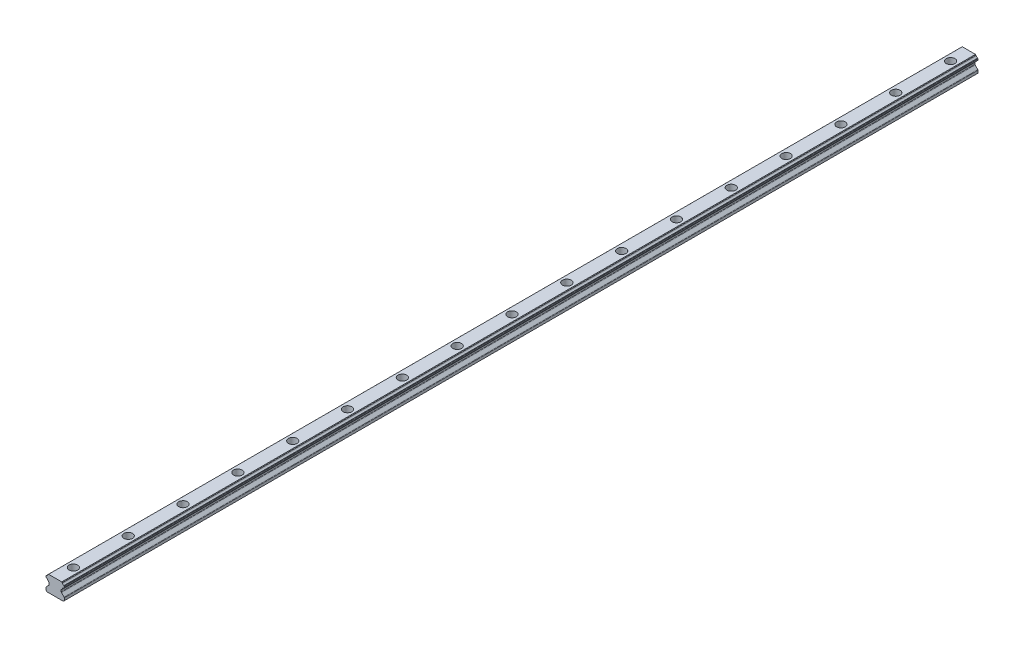
SolidWorks part; units mm, degrees
material "Stainless Steel (ferritic)"
ref_plane "Front Plane" through (0, 0, 0) normal (0, 0, 1) x (1, 0, 0)
ref_plane "Top Plane" through (0, 0, 0) normal (0, 1, 0) x (1, 0, 0)
ref_plane "Right Plane" through (0, 0, 0) normal (1, 0, 0) x (0, 0, -1)
sketch "Sketch10" plane through (0, 0, 0) normal (0, 0, 1) x (1, 0, 0)
  line L0 (-10, -10.3385) -> (-10, -13)
  line L1 (-10, -13) -> (-9, -14)
  line L2 (-9, -14) -> (9, -14)
  line L3 (6.8929, -6.8172) -> (9.7071, -9.6314)
  line L4 (6.6, -4.5499) -> (6.6, -6.1101)
  line L5 (7.6302, -3.1056) -> (6.8929, -3.8428)
  line L6 (9.8536, -0.8822) -> (9.6906, -1.0451)
  line L7 (10, 0.5286) -> (10, -0.5286)
  line L8 (9.6906, 1.0451) -> (9.8536, 0.8822)
  line L9 (7.2357, 3.5) -> (7.6325, 3.1032)
  line L10 (10, -13) -> (9, -14)
  line L11 (10, -10.3385) -> (10, -13)
  line L12 (7.2357, 3.5) -> (-7.2357, 3.5)
  line L13 (-7.2357, 3.5) -> (-7.6325, 3.1032)
  line L14 (-9.6906, 1.0451) -> (-9.8536, 0.8822)
  line L15 (-10, 0.5286) -> (-10, -0.5286)
  line L16 (-9.8536, -0.8822) -> (-9.6906, -1.0451)
  line L17 (-7.6302, -3.1056) -> (-6.8929, -3.8428)
  line L18 (-6.6, -4.5499) -> (-6.6, -6.1101)
  line L19 (-6.8929, -6.8172) -> (-9.7071, -9.6314)
  line L20 (0, -14) -> (0, 3.5) construction
  line L21 (-10, 0) -> (0, 0) construction
  arc A0 (-9.7071, -9.6314) -> (-10, -10.3385) centre (-9, -10.3385) ccw
  arc A1 (6.8929, -6.8172) -> (6.6, -6.1101) centre (7.6, -6.1101) cw
  arc A2 (6.6, -4.5499) -> (6.8929, -3.8428) centre (7.6, -4.5499) cw
  arc A3 (7.8468, -2.7675) -> (7.6302, -3.1056) centre (7.3529, -2.6895) cw
  arc A4 (7.8468, -2.7675) -> (9.4318, -1.1825) centre (9.8106, -3.1463) cw
  arc A5 (9.6906, -1.0451) -> (9.4318, -1.1825) centre (9.3371, -0.6915) cw
  arc A6 (10, -0.5286) -> (9.8536, -0.8822) centre (9.5, -0.5286) cw
  arc A7 (9.8536, 0.8822) -> (10, 0.5286) centre (9.5, 0.5286) cw
  arc A8 (9.4224, 1.1941) -> (9.6906, 1.0451) centre (9.3254, 0.7036) cw
  arc A9 (9.4224, 1.1941) -> (7.8482, 2.768) centre (9.8101, 3.1561) cw
  arc A10 (7.6325, 3.1032) -> (7.8482, 2.768) centre (7.3547, 2.6875) cw
  arc A11 (9.7071, -9.6314) -> (10, -10.3385) centre (9, -10.3385) cw
  arc A12 (-7.6325, 3.1032) -> (-7.8482, 2.768) centre (-7.3547, 2.6875) ccw
  arc A13 (-9.4224, 1.1941) -> (-7.8482, 2.768) centre (-9.8101, 3.1561) ccw
  arc A14 (-9.4224, 1.1941) -> (-9.6906, 1.0451) centre (-9.3254, 0.7036) ccw
  arc A15 (-9.8536, 0.8822) -> (-10, 0.5286) centre (-9.5, 0.5286) ccw
  arc A16 (-10, -0.5286) -> (-9.8536, -0.8822) centre (-9.5, -0.5286) ccw
  arc A17 (-9.6906, -1.0451) -> (-9.4318, -1.1825) centre (-9.3371, -0.6915) ccw
  arc A18 (-7.8468, -2.7675) -> (-9.4318, -1.1825) centre (-9.8106, -3.1463) ccw
  arc A19 (-7.8468, -2.7675) -> (-7.6302, -3.1056) centre (-7.3529, -2.6895) ccw
  arc A20 (-6.6, -4.5499) -> (-6.8929, -3.8428) centre (-7.6, -4.5499) ccw
  arc A21 (-6.8929, -6.8172) -> (-6.6, -6.1101) centre (-7.6, -6.1101) ccw
  dimension "D3" = 17.5
  dimension "D4" = 135
  dimension "D1" = 3.5
  dimension "D2" = 1
  dimension "D5" = 14
extrude "BODY" add sketch "Sketch10" along normal mid plane 1000
hole_wizard "CBORE for M6 SHCS1" positions "Sketch12" profile "Sketch11" counterbore size "M6" standard "ANSI Metric" end condition through all
sketch "Sketch12" plane through (0, 3.5, 0) normal (0, 1, 0) x (1, 0, 0)
  line L0 (0, -500) -> (0, -480) construction
  line L2 (7.2357, -500) -> (-7.2357, -500) construction
  point P0 (0, -480)
  dimension "D1" = 20
sketch "Sketch11" plane through (0, 3.5, 480) normal (1, 0, 0) x (0, 0, 1)
  line L0 (0, 0) -> (0, 17.5)
  line L1 (0, 17.5) -> (3, 17.5)
  line L3 (3, 17.5) -> (3, 8.4)
  line L4 (3, 8.4) -> (4.75, 8.4)
  line L5 (4.75, 8.4) -> (4.75, 0)
  line L7 (4.75, 0) -> (0, 0)
  line L11 (0, -6.35) -> (0, 107.95) construction
  dimension "Thru Hole Dia." = 6
  dimension "Thru Hole Depth" = 17.5
  dimension "C'Bore Dia." = 9.5
  dimension "C'Bore Depth" = 8.4
mirror "MIRROR FIRST COUNTERBORE" about plane through (0, 0, 0) normal (0, 0, 1) of "CBORE for M6 SHCS1"
sketch "END TO END HOLES" plane through (0, 0, 0) normal (0, 1, 0) x (1, 0, 0)
  line L0 (0, -480) -> (0, 480) construction
  dimension "DISTANCE" = 960
pattern_linear "LP CBORE" count 17 spacing 60 along (0, 0, -1) of "CBORE for M6 SHCS1"
equation "\"D1@LP CBORE\"   = INT(\"DISTANCE@END TO END HOLES\"/60)+1"
